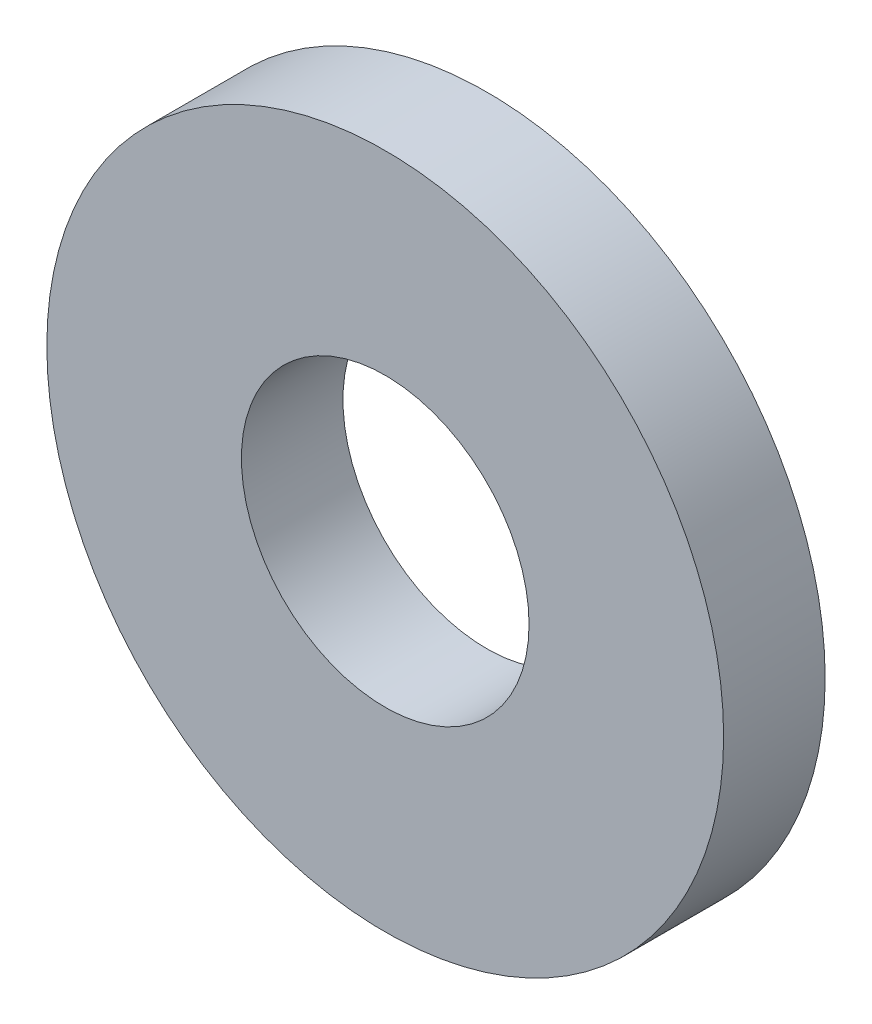
SolidWorks part; units mm, degrees
material "Plain Carbon Steel"
ref_plane "Front Plane" through (0, 0, 0) normal (0, 0, 1) x (1, 0, 0)
ref_plane "Top Plane" through (0, 0, 0) normal (0, 1, 0) x (1, 0, 0)
ref_plane "Right Plane" through (0, 0, 0) normal (1, 0, 0) x (0, 0, -1)
sketch "Sketch1" plane through (0, 0, 0) normal (0, 0, 1) x (1, 0, 0)
  line L0 (350, 49) -> (350, 125) construction
  line L2 (-675, 125) -> (675, 125) construction
  line L4 (350, -26.675) -> (350, 26.675) construction
  line L6 (350, 107) -> (350, 58.5) construction
  line L7 (314, 49) -> (389, 49) construction
  circle A0 centre (350, 87) radius 20
  circle A1 centre (350, 87) radius 8.5
  dimension "D1" = 40
  dimension "D2" = 17
extrude "Boss-Extrude1" add sketch "Sketch1" along normal blind 6
ref_point "Point1"
ref_plane "Plane1" through (350, 0, 0) normal (1, 0, 0) x (0, 0, -1)
ref_plane "Plane2" through (175, 0, 0) normal (1, 0, 0) x (0, 0, -1)
